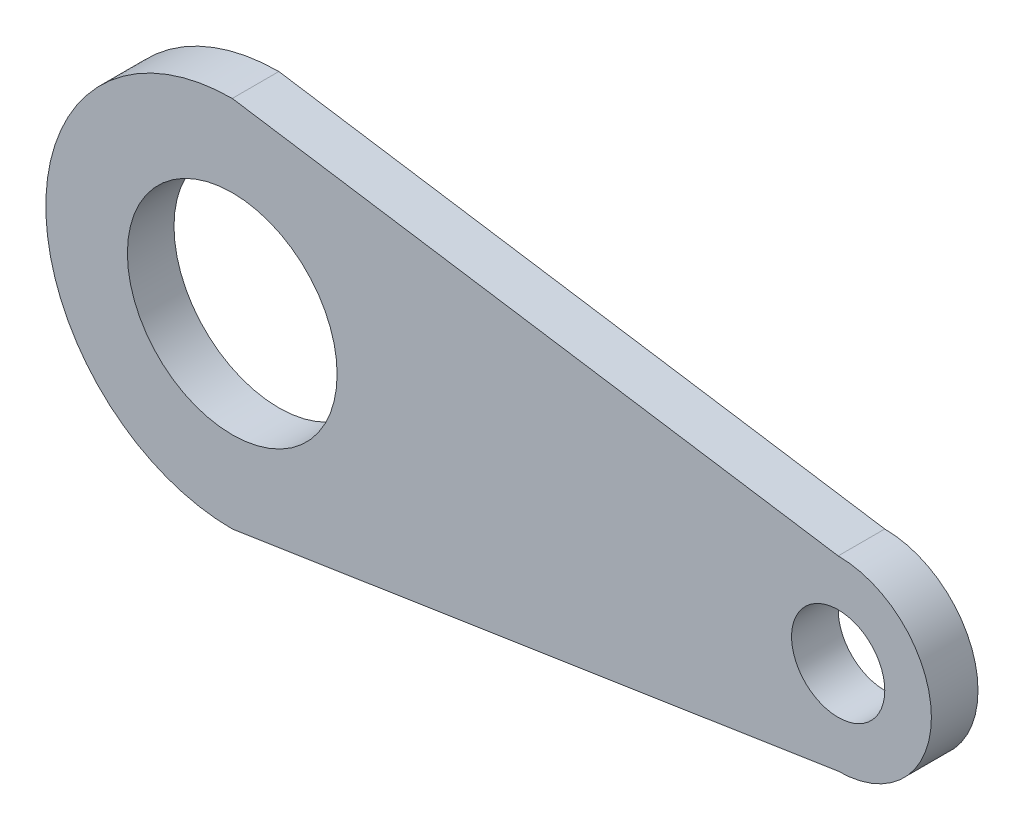
SolidWorks part; units mm, degrees
ref_plane "Front Plane" through (0, 0, 0) normal (0, 0, 1) x (1, 0, 0)
ref_plane "Top Plane" through (0, 0, 0) normal (0, 1, 0) x (1, 0, 0)
ref_plane "Right Plane" through (0, 0, 0) normal (1, 0, 0) x (0, 0, -1)
sketch "Sketch1" plane through (0, 0, 0) normal (0, 0, 1) x (1, 0, 0)
  line L5 (-57.0433, 40) -> (72.9567, 20)
  line L6 (-57.0433, -40) -> (72.9567, -20)
  circle A0 centre (72.9567, 0) radius 10
  arc A1 (-57.0433, 40) -> (-57.0433, -40) centre (-57.0433, 0) ccw
  circle A2 centre (-57.0433, 0) radius 22.5
  arc A3 (72.9567, -20) -> (72.9567, 20) centre (72.9567, 0) ccw
  dimension "D2" = 45
  dimension "D3" = 80
  dimension "D4" = 20
  dimension "D5" = 40
  dimension "D1" = 130
extrude "Boss-Extrude1" add sketch "Sketch1" along normal blind 10
